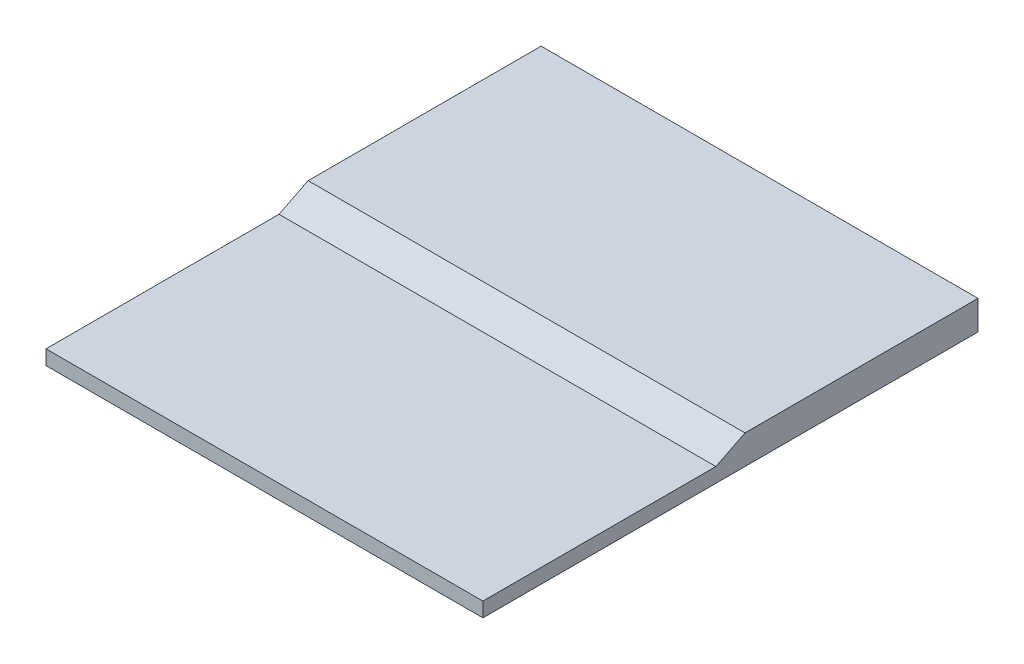
SolidWorks part; units mm, degrees
ref_plane "Front Plane" through (0, 0, 0) normal (0, 0, 1) x (1, 0, 0)
ref_plane "Top Plane" through (0, 0, 0) normal (0, 1, 0) x (1, 0, 0)
ref_plane "Right Plane" through (0, 0, 0) normal (1, 0, 0) x (0, 0, -1)
sketch "Sketch1" plane through (0, 0, 0) normal (1, 0, 0) x (0, 0, -1)
  line L0 (-406.4, 0) -> (0, 0)
  line L1 (0, 0) -> (50.8, 25.4)
  line L2 (50.8, 25.4) -> (457.2, 25.4)
  line L3 (457.2, 25.4) -> (457.2, -25.4)
  line L4 (457.2, -25.4) -> (-406.4, -25.4)
  line L5 (-406.4, -25.4) -> (-406.4, 0)
  line L6 (0, 0) -> (50.8, 0) construction
  line L7 (50.8, 0) -> (50.8, 25.4) construction
  dimension "D1" = 25.4
  dimension "D2" = 50.8
  dimension "D3" = 25.4
  dimension "D4" = 406.4
  dimension "D5" = 406.4
extrude "Boss-Extrude1" add sketch "Sketch1" along normal blind 762
